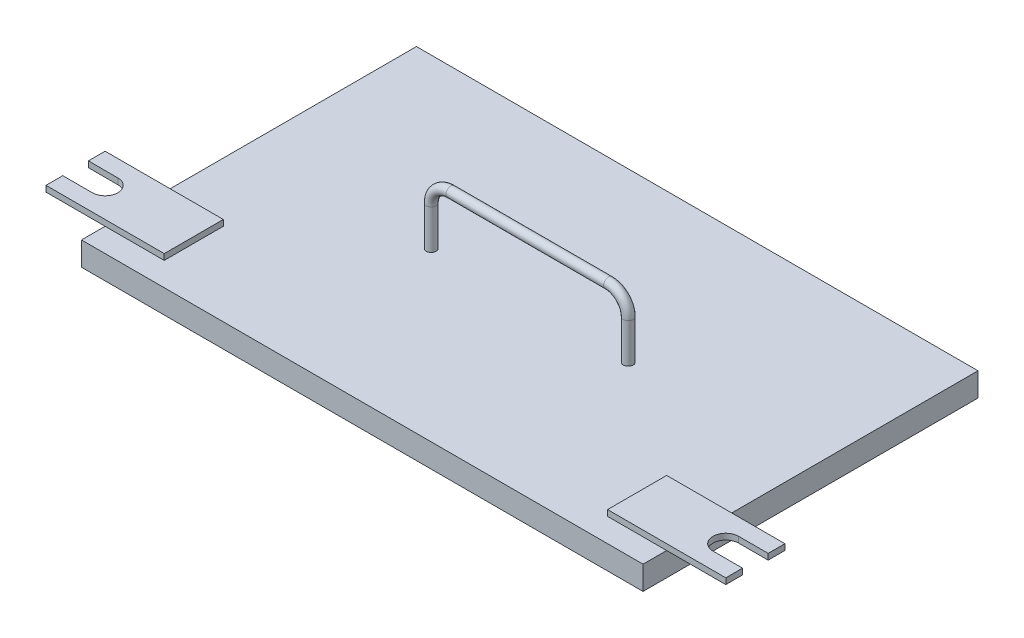
SolidWorks part; units mm, degrees
ref_plane "Front Plane" through (0, 0, 0) normal (0, 0, 1) x (1, 0, 0)
ref_plane "Top Plane" through (0, 0, 0) normal (0, 1, 0) x (1, 0, 0)
ref_plane "Right Plane" through (0, 0, 0) normal (1, 0, 0) x (0, 0, -1)
sketch "Sketch1" plane through (0, 0, 0) normal (0, 1, 0) x (1, 0, 0)
  line L1 (142.5, 85) -> (-142.5, 85)
  line L2 (142.5, 85) -> (142.5, -85)
  line L3 (142.5, -85) -> (-142.5, -85)
  line L4 (-142.5, 85) -> (-142.5, -85)
  line L5 (142.5, 85) -> (-142.5, -85) construction
  line L6 (142.5, -85) -> (-142.5, 85) construction
  point P0 (0, 0)
  dimension "D1" = 285
  dimension "D2" = 170
extrude "Boss-Extrude1" add sketch "Sketch1" along normal blind 12
sketch "Sketch2" plane through (0, 12, 0) normal (0, 1, 0) x (1, 0, 0)
  line L3 (142.5, 85) -> (-142.5, 85) construction
  circle A0 centre (-50, 0) radius 2.5
  dimension "D1" = 5
  dimension "D2" = 50
  dimension "D3" = 85
sketch "Sketch3" plane through (0, 0, 0) normal (0, 0, 1) x (1, 0, 0)
  line L0 (-50, 12) -> (-50, 32)
  line L1 (-47.5, 12) -> (-52.5, 12) construction
  line L4 (-40, 42) -> (40, 42)
  line L5 (50, 12) -> (50, 32)
  arc A0 (40, 42) -> (50, 32) centre (40, 32) cw
  arc A1 (-50, 32) -> (-40, 42) centre (-40, 32) cw
  point P14 (50, 42)
  point P17 (-50, 42)
  dimension "D2" = 10
  dimension "D1" = 30
  dimension "D3" = 100
  dimension "D4" = 30
sweep "Sweep1" add profiles "Sketch2" path "Sketch3"
sketch "Sketch4" plane through (0, 12, 0) normal (0, 1, 0) x (1, 0, 0)
  line L0 (142.5, -85) -> (142.5, 85) construction
  line L1 (112.5, -43) -> (172.5, -43)
  line L2 (112.5, -43) -> (112.5, -73)
  line L3 (112.5, -73) -> (172.5, -73)
  line L4 (172.5, -43) -> (172.5, -73)
  line L5 (112.5, -43) -> (172.5, -73) construction
  line L6 (112.5, -73) -> (172.5, -43) construction
  line L7 (-142.5, -85) -> (142.5, -85) construction
  line L8 (0, 0) -> (0, -85) construction
  line L9 (-112.5, -73) -> (-172.5, -43) construction
  line L10 (-112.5, -43) -> (-172.5, -73) construction
  line L11 (-172.5, -43) -> (-172.5, -73)
  line L12 (-112.5, -73) -> (-172.5, -73)
  line L13 (-112.5, -43) -> (-112.5, -73)
  line L14 (-112.5, -43) -> (-172.5, -43)
  point P0 (142.5, -58)
  point P17 (-142.5, -58)
  dimension "D1" = 30
  dimension "D2" = 30
  dimension "D3" = 12
extrude "Boss-Extrude2" add sketch "Sketch4" along normal blind 3
sketch "Sketch5" plane through (0, 15, 0) normal (0, 1, 0) x (1, 0, 0)
  line L0 (142.5, -43) -> (142.5, -73) construction
  line L1 (172.5, -43) -> (112.5, -43) construction
  line L2 (112.5, -73) -> (172.5, -73) construction
  line L3 (112.5, -58) -> (172.5, -58) construction
  line L4 (112.5, -43) -> (112.5, -73) construction
  line L5 (172.5, -73) -> (172.5, -43) construction
  line L6 (172.5, -58) -> (157.5, -58) construction
  line L7 (172.5, -64.5) -> (157.5, -64.5)
  line L8 (172.5, -51.5) -> (157.5, -51.5)
  line L9 (172.5, -51.5) -> (172.5, -64.5) construction
  arc A1 (157.5, -51.5) -> (157.5, -64.5) centre (157.5, -58) ccw
  point P12 (165, -58)
  dimension "D3" = 6.5
  dimension "D1" = 15
  dimension "D2" = 13
  dimension "D4" = 8.5
extrude "Cut-Extrude1" cut sketch "Sketch5" against normal through all and the other way through all
mirror "Mirror1" about plane through (0, 0, 0) normal (1, 0, 0) of "Cut-Extrude1"
